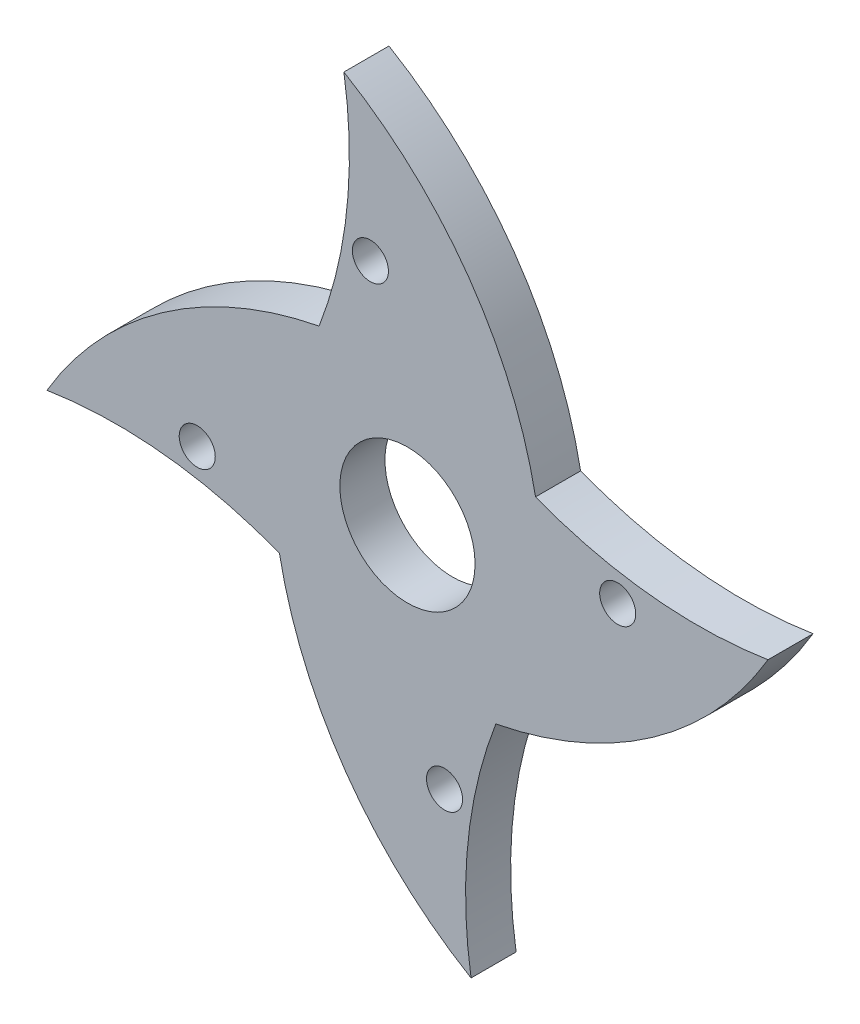
SolidWorks part; units mm, degrees
ref_plane "Alzado" through (0, 0, 0) normal (0, 0, 1) x (1, 0, 0)
ref_plane "Planta" through (0, 0, 0) normal (0, 1, 0) x (1, 0, 0)
ref_plane "Vista lateral" through (0, 0, 0) normal (1, 0, 0) x (0, 0, -1)
sketch "Croquis1" plane through (0, 0, 0) normal (0, 0, 1) x (1, 0, 0)
  line L0 (0, 0) -> (-56.2335, 0) construction
  line L1 (0, 0) -> (-14.1062, 80) construction
  circle A0 centre (0, 0) radius 15
  circle A1 centre (0, 0) radius 30
  circle A2 centre (-8.2257, 46.65) radius 4
  arc A3 (-14.1062, 80) -> (28.42, 19.61) centre (-59.9483, 2.55) cw
  arc A4 (-14.1062, 80) -> (-19.61, 28.42) centre (-112.8909, 64.4572) cw
  arc A5 (80, 14.1062) -> (19.61, -28.42) centre (2.55, 59.9483) cw
  arc A6 (80, 14.1062) -> (28.42, 19.61) centre (64.4572, 112.8909) cw
  circle A7 centre (46.65, 8.2257) radius 4
  arc A8 (14.1062, -80) -> (-28.42, -19.61) centre (59.9483, -2.55) cw
  arc A9 (14.1062, -80) -> (19.61, -28.42) centre (112.8909, -64.4572) cw
  circle A10 centre (8.2257, -46.65) radius 4
  arc A11 (-80, -14.1062) -> (-19.61, 28.42) centre (-2.55, -59.9483) cw
  arc A12 (-80, -14.1062) -> (-28.42, -19.61) centre (-64.4572, -112.8909) cw
  circle A13 centre (-46.65, -8.2257) radius 4
  point P36 (0, 0)
  dimension "D1" = 60
  dimension "D2" = 30
  dimension "D5" = 90
  dimension "D7" = 8
  dimension "D6" = 100
  dimension "D3" = 80
  dimension "D4" = 80
  dimension "D8" = 46.65
  dimension "D9" = 19.61
  dimension "D10" = 28.42
  dimension "D11" = 19.61
  dimension "D12" = 28.42
  dimension "D13" = 4
extrude "Saliente-Extruir2" add sketch "Croquis1" along normal blind 10 contours A11 A12 A8 A9 A5 A6 A3 A4 A13 A1 A2 A7 A10 | A1 A0
